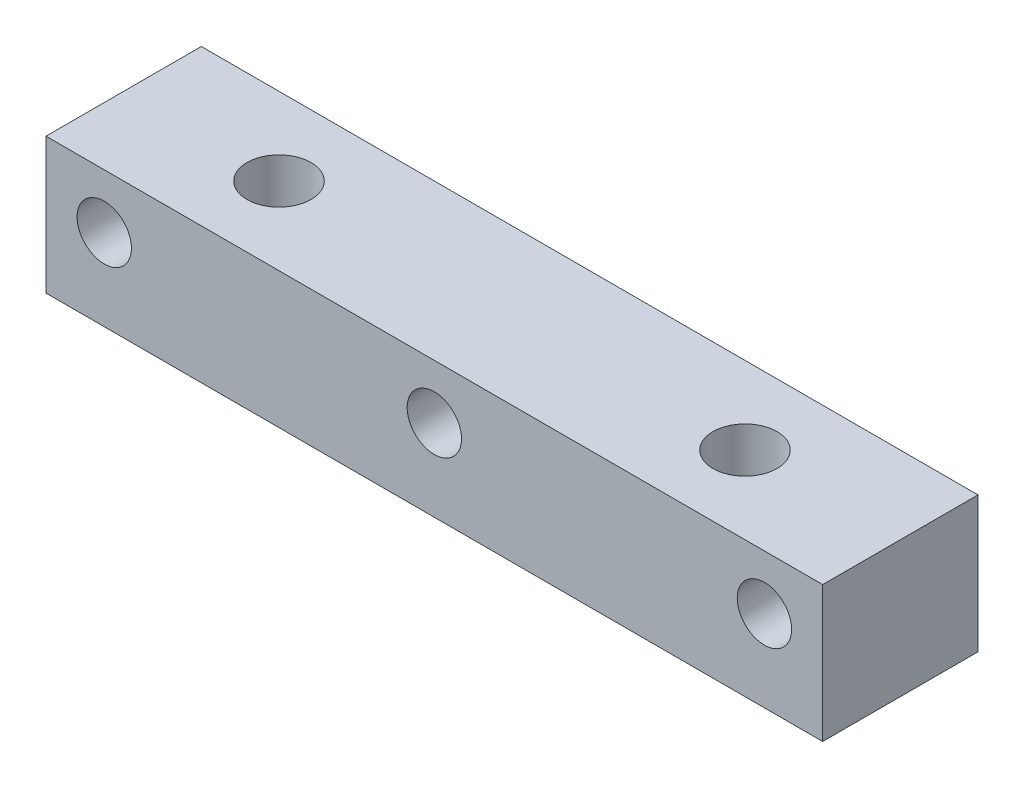
SolidWorks part; units mm, degrees
ref_plane "Front" through (0, 0, 0) normal (0, 0, 1) x (1, 0, 0)
ref_plane "Top" through (0, 0, 0) normal (0, 1, 0) x (1, 0, 0)
ref_plane "Right" through (0, 0, 0) normal (1, 0, 0) x (0, 0, -1)
sketch "Esquisse1" plane through (0, 0, 0) normal (0, 0, 1) x (1, 0, 0)
  line L1 (0, 0) -> (40, 0)
  line L2 (0, 0) -> (0, 7)
  line L3 (0, 7) -> (40, 7)
  line L4 (40, 0) -> (40, 7)
  dimension "D1" = 7
  dimension "D2" = 40
extrude "Boss.-Extru.1" add sketch "Esquisse1" along normal blind 8
sketch "Esquisse2" plane through (0, 0, 8) normal (0, 0, 1) x (1, 0, 0)
  line L0 (20, 0) -> (20, 7) construction
  line L1 (0, 0) -> (40, 0) construction
  line L2 (40, 7) -> (0, 7) construction
  line L3 (3, 4.2) -> (20, 4.2) construction
  circle A0 centre (20, 4.2) radius 1.4
  circle A1 centre (3, 4.2) radius 1.4
  circle A2 centre (37, 4.2) radius 1.4
  dimension "D1" = 17
  dimension "D2" = 2.8
  dimension "D3" = 4.2
extrude "Enlèv. mat.-Extru.1" cut sketch "Esquisse2" against normal through all
sketch "Esquisse3" plane through (0, 7, 0) normal (0, 1, 0) x (1, 0, 0)
  line L0 (20, -8) -> (20, 0) construction
  line L1 (40, -8) -> (0, -8) construction
  line L2 (40, 0) -> (0, 0) construction
  line L3 (8, -4) -> (20, -4) construction
  circle A0 centre (8, -4) radius 1.65
  circle A1 centre (32, -4) radius 1.65
  dimension "D1" = 24
  dimension "D2" = 3.3
extrude "Enlèv. mat.-Extru.2" cut sketch "Esquisse3" against normal through all
